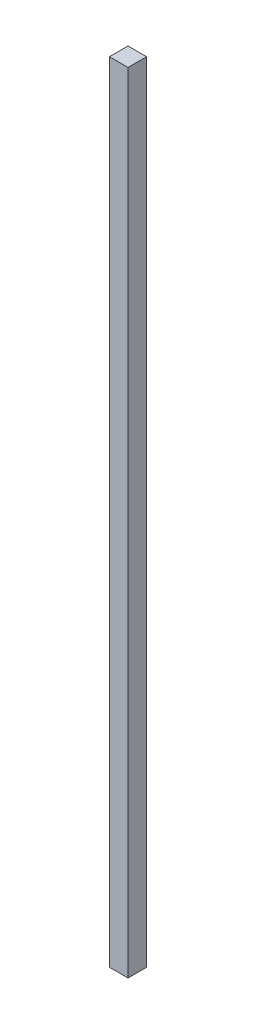
SolidWorks part; units mm, degrees
ref_plane "Front Plane" through (0, 0, 0) normal (0, 0, 1) x (1, 0, 0)
ref_plane "Top Plane" through (0, 0, 0) normal (0, 1, 0) x (1, 0, 0)
ref_plane "Right Plane" through (0, 0, 0) normal (1, 0, 0) x (0, 0, -1)
sketch "Sketch1" plane through (0, 0, 0) normal (0, 1, 0) x (1, 0, 0)
  line L1 (-10, 10) -> (10, 10)
  line L2 (-10, 10) -> (-10, -10)
  line L3 (-10, -10) -> (10, -10)
  line L4 (10, 10) -> (10, -10)
  line L5 (-10, 10) -> (10, -10) construction
  line L6 (-10, -10) -> (10, 10) construction
  point P0 (0, 0)
  dimension "D1" = 20
  dimension "D2" = 20
extrude "Boss-Extrude1" add sketch "Sketch1" along normal blind 850
